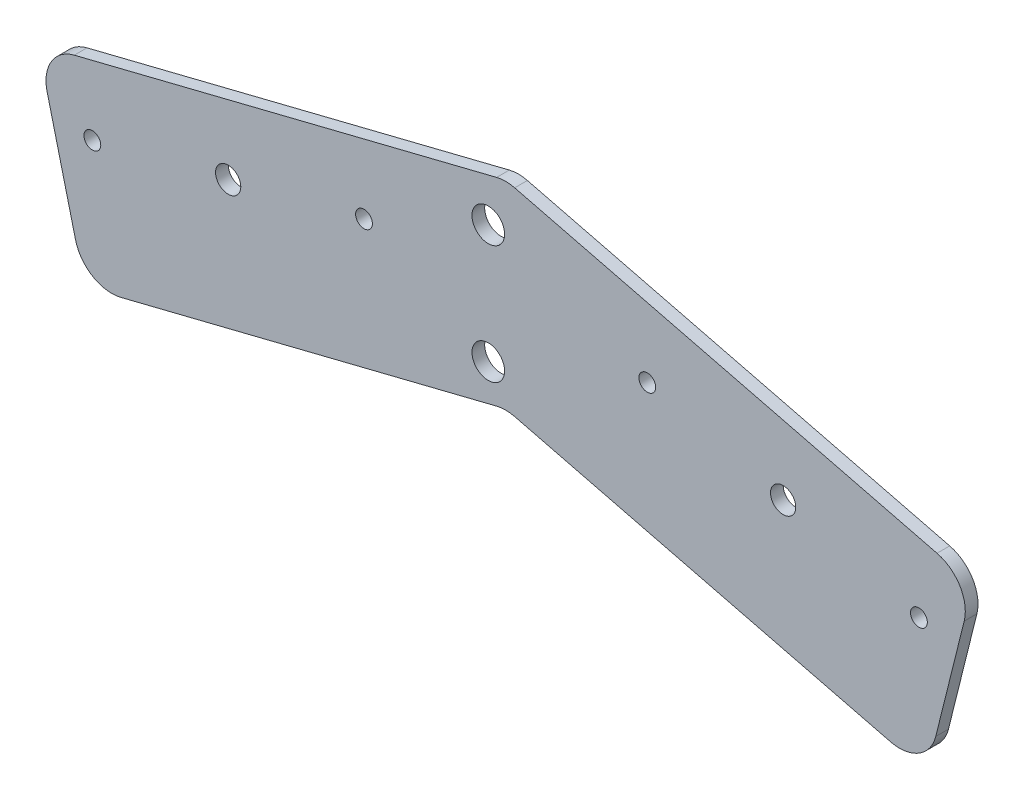
SolidWorks part; units mm, degrees
ref_plane "Front Plane" through (0, 0, 0) normal (0, 0, 1) x (1, 0, 0)
ref_plane "Top Plane" through (0, 0, 0) normal (0, 1, 0) x (1, 0, 0)
ref_plane "Right Plane" through (0, 0, 0) normal (1, 0, 0) x (0, 0, -1)
sketch "Sketch1" plane through (0, 0, 0) normal (0, 0, 1) x (1, 0, 0)
  line L0 (0, 0) -> (-82.5, -20.5696) construction
  line L1 (0, 0) -> (82.5, -20.5696) construction
  line L2 (-82.5, -20.5696) -> (82.5, -20.5696) construction
  line L3 (-82.5, -20.5696) -> (-74.3351, -53.317) construction
  line L4 (82.5, -20.5696) -> (74.3351, -53.317) construction
  line L5 (-74.3351, -53.317) -> (-37.949, -44.245) construction
  line L6 (-74.3351, -53.317) -> (-110.7212, -62.3891) construction
  line L7 (74.3351, -53.317) -> (37.949, -44.245) construction
  line L8 (74.3351, -53.317) -> (110.7212, -62.3891) construction
  line L9 (55, 0) -> (-55, 0) construction
  line L10 (-115.561, -45.0447) -> (-2.4192, -16.8353)
  line L11 (2.4192, -16.8353) -> (115.561, -45.0447)
  line L12 (122.8447, -57.1669) -> (115.2242, -87.7312)
  line L13 (103.102, -95.015) -> (2.4192, -69.9119)
  line L14 (-2.4192, -69.9119) -> (-103.102, -95.015)
  line L15 (-115.2242, -87.7312) -> (-122.8447, -57.1669)
  line L16 (0, -20.5696) -> (0, -58.6696) construction
  line L17 (-4.6482, -20.5696) -> (-4.6482, -60.7016) construction
  arc A0 (-2.4192, -16.8353) -> (2.4192, -16.8353) centre (0, -26.5383) cw
  arc A1 (2.4192, -69.9119) -> (-2.4192, -69.9119) centre (0, -79.6149) ccw
  arc A2 (115.561, -45.0447) -> (122.8447, -57.1669) centre (113.1417, -54.7477) cw
  arc A3 (115.2242, -87.7312) -> (103.102, -95.015) centre (105.5212, -85.312) cw
  arc A4 (-103.102, -95.015) -> (-115.2242, -87.7312) centre (-105.5212, -85.312) cw
  arc A5 (-115.561, -45.0447) -> (-122.8447, -57.1669) centre (-113.1417, -54.7477) ccw
  point P17 (-4.6482, -28.9516)
  point P21 (0, -16.2322)
  point P24 (0, -69.3088)
  dimension "D13" = 10
  dimension "D1" = 165
  dimension "D2" = 18
  dimension "D3" = 152
  dimension "D4" = 33.75
  dimension "D5" = 33.75
  dimension "D6" = 37.5
  dimension "D7" = 37.5
  dimension "D8" = 37.5
  dimension "D9" = 37.5
  dimension "D10" = 33.5
  dimension "D11" = 48
  dimension "D12" = 48
  dimension "D14" = 4.6482
  dimension "D15" = 40.132
  dimension "D16" = 31.75
extrude "Boss-Extrude1" add sketch "Sketch1" against normal blind 3.4036
hole_wizard "1/4 Clearance Hole1" positions "Sketch9" profile "Sketch10" hole size "1/4" standard "ANSI Inch" end condition through all
sketch "Sketch9" plane through (0, 0, 0) normal (0, 0, 1) x (1, 0, 0)
  point P0 (-74.3351, -53.317)
  point P3 (74.3351, -53.317)
sketch "Sketch10" plane through (-74.3351, -53.317, 0) normal (1, 0, 0) x (0, -1, 0)
  line L0 (0, 0) -> (0, 3.4036)
  line L1 (0, 3.4036) -> (3.3782, 3.4036)
  line L2 (3.3782, 3.4036) -> (3.3782, 0)
  line L5 (3.3782, 0) -> (0, 0)
  line L11 (0, -6.35) -> (0, 107.95) construction
  dimension "Thru Hole Dia." = 6.7564
  dimension "Thru Hole Depth" = 3.4036
hole_wizard "M4 Clearance Hole1" positions "Sketch11" profile "Sketch12" hole size "M4" standard "ANSI Metric" end condition through all
sketch "Sketch11" plane through (0, 0, 0) normal (0, 0, 1) x (1, 0, 0)
  point P0 (-110.7212, -62.3891)
  point P3 (-37.949, -44.245)
  point P6 (37.949, -44.245)
  point P9 (110.7212, -62.3891)
sketch "Sketch12" plane through (-110.7212, -62.3891, 0) normal (1, 0, 0) x (0, -1, 0)
  line L0 (0, 0) -> (0, 3.4036)
  line L1 (0, 3.4036) -> (2.25, 3.4036)
  line L2 (2.25, 3.4036) -> (2.25, 0)
  line L5 (2.25, 0) -> (0, 0)
  line L11 (0, -6.35) -> (0, 107.95) construction
  dimension "Thru Hole Dia." = 4.5
  dimension "Thru Hole Depth" = 3.4036
hole_wizard "Hole for 1/4 300® SC Nuts (SP)1" positions "Sketch13" profile "Sketch14" hole size "1/4-20" standard "PEM® Inch" end condition through all
sketch "Sketch13" plane through (0, 0, 0) normal (0, 0, 1) x (1, 0, 0)
  point P20 (-4.6482, -60.7016)
  point P23 (-4.6482, -28.9516)
sketch "Sketch14" plane through (-4.6482, -60.7016, 0) normal (1, 0, 0) x (0, -1, 0)
  line L0 (0, 0) -> (0, 3.4036)
  line L1 (0, 3.4036) -> (4.3688, 3.4036)
  line L2 (4.3688, 3.4036) -> (4.3688, 0)
  line L5 (4.3688, 0) -> (0, 0)
  line L11 (0, -6.35) -> (0, 107.95) construction
  dimension "Thru Hole Dia." = 8.7376
  dimension "Thru Hole Depth" = 3.4036
